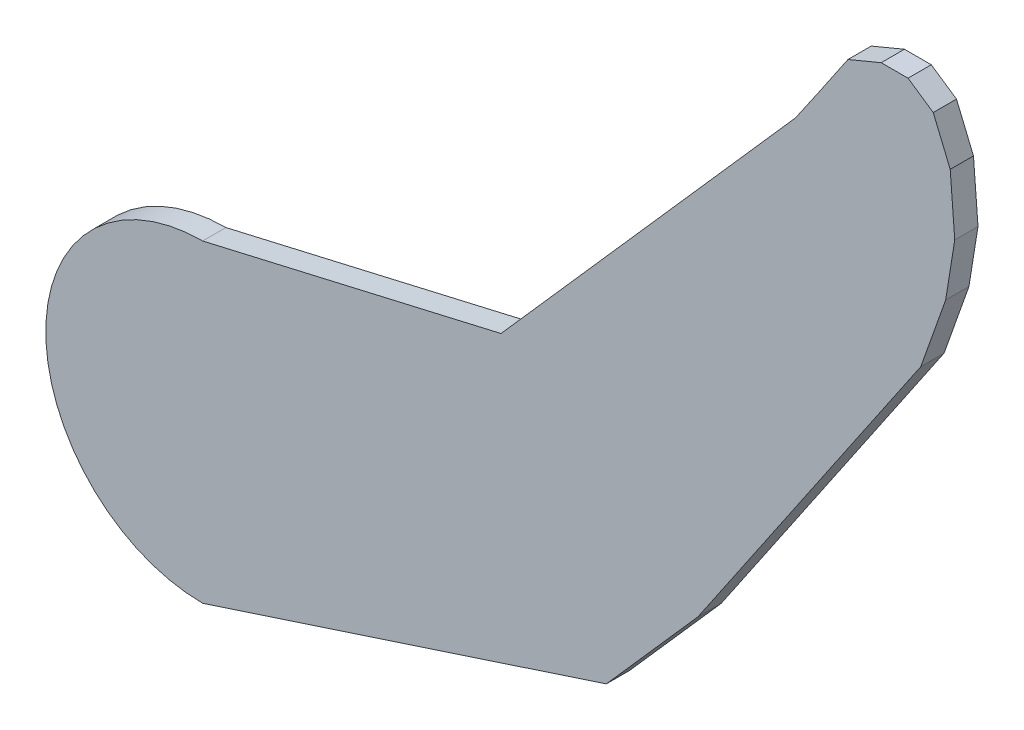
SolidWorks part; units mm, degrees
ref_plane "Alzado" through (0, 0, 0) normal (0, 0, 1) x (1, 0, 0)
ref_plane "Planta" through (0, 0, 0) normal (0, 1, 0) x (1, 0, 0)
ref_plane "Vista lateral" through (0, 0, 0) normal (1, 0, 0) x (0, 0, -1)
sketch "Croquis1" plane through (0, 0, 0) normal (0, 0, 1) x (1, 0, 0)
  line L2 (853.0701, 88.1693) -> (931.8511, 177.5173)
  line L3 (931.8511, 177.5173) -> (1123.4323, 459.5748)
  line L4 (1123.4323, 459.5748) -> (1144.8341, 519.8889)
  line L5 (1144.8341, 519.8889) -> (1152.6166, 568.5294)
  line L6 (1152.6166, 568.5294) -> (1148.7253, 619.1154)
  line L7 (1148.7253, 619.1154) -> (1134.1332, 654.1366)
  line L8 (1134.1332, 654.1366) -> (1112.467, 668.8528)
  line L9 (1015.7689, 590.989) -> (762.5542, 303.8102)
  line L10 (762.5542, 303.8102) -> (506.0783, 244.4681)
  line L11 (1112.467, 668.8528) -> (1089.384, 668.8528)
  line L12 (1089.384, 668.8528) -> (1060.8119, 656.9478)
  line L13 (1060.8119, 656.9478) -> (1035.1151, 619.1154)
  line L14 (1015.7689, 590.989) -> (1035.1151, 619.1154)
  line L15 (853.0701, 88.1693) -> (506.0783, -25.2429)
  arc A4 (506.0783, 244.4681) -> (506.0783, -25.2429) centre (506.0783, 109.6126) ccw
  dimension "D2" = 382.8699
  dimension "D6" = 161.779
  dimension "D19" = 134.8555
  dimension "D1" = 263.2515
  dimension "D3" = 340.9689
  dimension "D4" = 119.1197
  dimension "D5" = 365.0556
  dimension "D7" = 146.805
  dimension "D8" = 63.9987
  dimension "D9" = 49.2591
  dimension "D10" = 50.7355
  dimension "D11" = 37.9396
  dimension "D12" = 26.1915
  dimension "D13" = 23.083
  dimension "D14" = 30.9531
  dimension "D15" = 45.7341
  dimension "D16" = 34.1376
  dimension "D17" = 186.882
  dimension "D18" = 215.569
  dimension "D20" = 172.782
  dimension "D21" = 165.351
  dimension "D22" = 169.554
  dimension "D23" = 166.511
  dimension "D24" = 149.503
  dimension "D26" = 157.38
  dimension "D27" = 146.805
extrude "Saliente-Extruir1" add sketch "Croquis1" along normal blind 20
